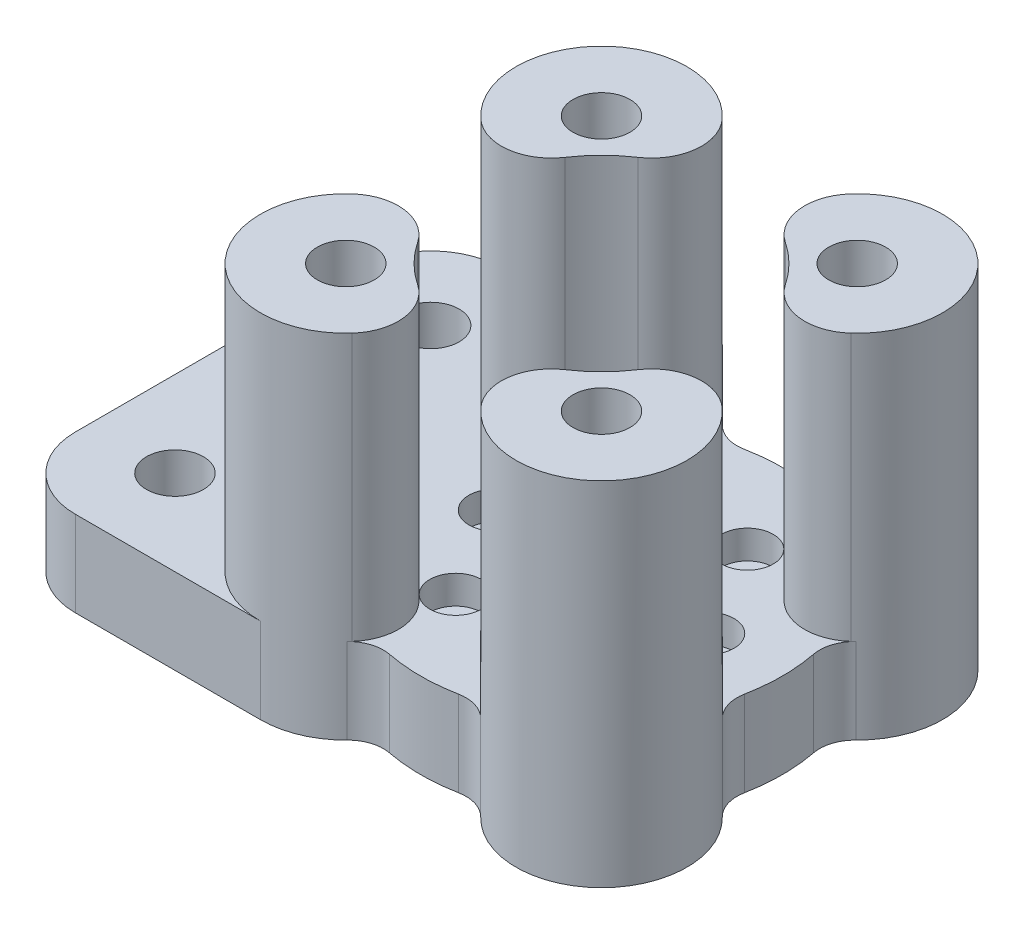
SolidWorks part; units mm, degrees
material "1060 Alloy"
ref_plane "Front" through (0, 0, 0) normal (0, 0, 1) x (1, 0, 0)
ref_plane "Top" through (0, 0, 0) normal (0, 1, 0) x (1, 0, 0)
ref_plane "Right" through (0, 0, 0) normal (1, 0, 0) x (0, 0, -1)
sketch "Sketch1" plane through (0, 0, 0) normal (0, 1, 0) x (1, 0, 0)
  line L0 (0, 0) -> (-17.9605, 17.9605) construction
  line L1 (0, 0) -> (0, 25.4) construction
  line L2 (0, 0) -> (-7.5, 12.9904) construction
  line L3 (-17.9605, 29.9605) -> (-43.9605, 29.9605)
  line L4 (-53.9605, 19.9605) -> (-53.9605, -19.9605)
  line L5 (-43.9605, -29.9605) -> (-17.9605, -29.9605)
  circle A0 centre (-17.9605, 17.9605) radius 4
  circle A1 centre (17.9605, 17.9605) radius 4
  circle A2 centre (17.9605, -17.9605) radius 4
  circle A3 centre (-17.9605, -17.9605) radius 4
  circle A4 centre (0, 0) radius 10.5
  arc A5 (-9.3775, 26.347) -> (-26.347, 9.3775) centre (-17.9605, 17.9605) ccw construction
  arc A6 (26.347, 9.3775) -> (9.3775, 26.347) centre (17.9605, 17.9605) ccw
  arc A7 (9.3775, -26.347) -> (26.347, -9.3775) centre (17.9605, -17.9605) ccw
  arc A8 (-26.347, -9.3775) -> (-9.3775, -26.347) centre (-17.9605, -17.9605) ccw construction
  arc A9 (-24.9332, 4.8471) -> (-24.9332, -4.8471) centre (0, 0) ccw construction
  arc A10 (-4.8471, -24.9332) -> (4.8471, -24.9332) centre (0, 0) ccw
  arc A11 (24.9332, -4.8471) -> (24.9332, 4.8471) centre (0, 0) ccw
  arc A12 (-4.8471, 24.9332) -> (-9.3775, 26.347) centre (-5.8013, 29.8413) cw
  arc A13 (4.8471, 24.9332) -> (-4.8471, 24.9332) centre (0, 0) ccw
  arc A14 (9.3775, 26.347) -> (4.8471, 24.9332) centre (5.8013, 29.8413) cw
  arc A15 (26.347, 9.3775) -> (24.9332, 4.8471) centre (29.8413, 5.8013) ccw
  arc A16 (24.9332, -4.8471) -> (26.347, -9.3775) centre (29.8413, -5.8013) ccw
  arc A17 (9.3775, -26.347) -> (4.8471, -24.9332) centre (5.8013, -29.8413) ccw
  arc A18 (-4.8471, -24.9332) -> (-9.3775, -26.347) centre (-5.8013, -29.8413) ccw
  arc A19 (-24.9332, -4.8471) -> (-26.347, -9.3775) centre (-29.8413, -5.8013) cw construction
  arc A20 (-24.9332, 4.8471) -> (-26.347, 9.3775) centre (-29.8413, 5.8013) ccw construction
  circle A21 centre (0, 0) radius 15 construction
  circle A22 centre (-7.5, 12.9904) radius 2
  circle A23 centre (7.5, 12.9904) radius 2
  circle A24 centre (15, 0) radius 2
  circle A25 centre (7.5, -12.9904) radius 2
  circle A26 centre (-7.5, -12.9904) radius 2
  circle A27 centre (-15, 0) radius 2
  arc A28 (-9.3775, 26.347) -> (-17.9605, 29.9605) centre (-17.9605, 17.9605) ccw
  arc A29 (-9.3775, -26.347) -> (-17.9605, -29.9605) centre (-17.9605, -17.9605) cw
  circle A30 centre (-41.9605, 17.9605) radius 4
  circle A31 centre (-41.9605, -17.9605) radius 4
  arc A32 (-53.9605, -19.9605) -> (-43.9605, -29.9605) centre (-43.9605, -19.9605) ccw
  arc A33 (-43.9605, 29.9605) -> (-53.9605, 19.9605) centre (-43.9605, 19.9605) ccw
  point P0 (0, 0)
  point P17 (0, 0)
  point P27 (0, 0)
  point P56 (0, 0)
  dimension "D5" = 8
  dimension "D6" = 21
  dimension "D1" = 5
  dimension "D7" = 12
  dimension "D9" = 30
  dimension "D11" = 4
  dimension "D14" = 10
  dimension "D3" = 25.4
  dimension "D2" = 12
  dimension "D10" = 12
  dimension "D13" = 24
  dimension "D4" = 4
  dimension "D8" = 4
  dimension "D12" = 6
extrude "base" add sketch "Sketch1" along normal blind 12
sketch "Sketch2" plane through (0, 12, 0) normal (0, 1, 0) x (1, 0, 0)
  circle A0 centre (0, 0) radius 15 construction
  circle A1 centre (-7.5, 12.9904) radius 3.625
  circle A2 centre (7.5, 12.9904) radius 3.625
  circle A3 centre (15, 0) radius 3.625
  circle A4 centre (7.5, -12.9904) radius 3.625
  circle A5 centre (-7.5, -12.9904) radius 3.625
  circle A7 centre (-15, 0) radius 3.625
  point P15 (0, 0)
  point P17 (0, 0)
  dimension "D1" = 7.25
  dimension "D2" = 6
extrude "bolt head recesses" cut sketch "Sketch2" against normal blind 4
sketch "Sketch3" plane through (0, 12, 0) normal (0, 1, 0) x (1, 0, 0)
  circle A0 centre (-17.9605, -17.9605) radius 4
  arc A1 (-17.6441, -5.9647) -> (-5.9647, -17.6441) centre (-17.9605, -17.9605) ccw
  circle A2 centre (-17.9605, -17.9605) radius 4 construction
  arc A4 (-5.9647, 17.6441) -> (-17.6441, 5.9647) centre (-17.9605, 17.9605) ccw
  circle A5 centre (-17.9605, 17.9605) radius 4
  arc A6 (17.6441, 5.9647) -> (5.9647, 17.6441) centre (17.9605, 17.9605) ccw
  circle A7 centre (17.9605, 17.9605) radius 4
  arc A8 (5.9647, -17.6441) -> (17.6441, -5.9647) centre (17.9605, -17.9605) ccw
  circle A9 centre (17.9605, -17.9605) radius 4
  circle A10 centre (0, 0) radius 25.4 construction
  arc A11 (-17.6441, -5.9647) -> (-5.9647, -17.6441) centre (0, 0) ccw
  circle A12 centre (-7.5, 12.9904) radius 3.625 construction
  arc A13 (-5.9647, 17.6441) -> (-17.6441, 5.9647) centre (0, 0) ccw
  arc A14 (17.6441, 5.9647) -> (5.9647, 17.6441) centre (0, 0) ccw
  arc A15 (5.9647, -17.6441) -> (17.6441, -5.9647) centre (0, 0) ccw
  arc A16 (-17.9605, -29.9605) -> (-9.3775, -26.347) centre (-17.9605, -17.9605) ccw construction
  point P21 (0, 0)
  dimension "D1" = 4
extrude "legs" add sketch "Sketch3" along normal blind 37.5
fillet "Fillet2" radius 7 8 edges at (-17.6441, 30.75, 5.9647) (-5.9647, 30.75, 17.6441) (17.6441, 30.75, 5.9647) (5.9647, 30.75, 17.6441) (17.6441, 30.75, -5.9647) (5.9647, 30.75, -17.6441) (-17.6441, 30.75, -5.9647) (-5.9647, 30.75, -17.6441)
sketch "Sketch4" plane through (0, 0, 0) normal (0, -1, 0) x (1, 0, 0)
  circle A0 centre (0, 0) radius 25.4 construction
  circle A1 centre (17.9605, 17.9605) radius 7
  circle A2 centre (17.9605, -17.9605) radius 7
  circle A3 centre (-17.9605, -17.9605) radius 7
  circle A4 centre (-17.9605, 17.9605) radius 7
  point P16 (0, 0)
  dimension "D1" = 14
  dimension "D2" = 4
extrude "m8 counterbore" cut sketch "Sketch4" against normal blind 8
equation "\"D3@Sketch1\"=\"square plate bolt pattern diameter\"/2"
equation "\"D1@base\" = \"motor mount plate thickness\""
equation "\"D5@Sketch1\"=\"square plate bolt hole ID\""
equation "\"D6@Sketch1\"=\"motor mount coupler hole diameter\""
equation "\"bearing OD\" = 30mm"
equation "\"bearing outer race thickness\"= 1mm"
equation "\"bearing ID\"= 10mm"
equation "\"bearing depth\"= 9mm"
equation "\"bearing inner race thickness\"= 1mm"
equation "\"small seal OD\" = 20mm"
equation "\"small seal ID\"= 8mm"
equation "\"small seal depth\" = 8.3mm"
equation "\"big seal OD\" = 27mm"
equation "\"big seal ID\"= 15mm"
equation "\"big seal depth\"= 8.3mm"
equation "\"z\" = 8 \t\t\t\t'number of blades"
equation "\"de\" = 0.426in \t\t\t\t'entrance eye diameter"
equation "\"d2\" = 2.097in \t\t\t\t'outer diameter of the impeller "
equation "\"d_exit\" = 0.18in \t\t\t'volute throat aka D4"
equation "\"theta\" = 15"
equation "\"b2\" = .071in\t\t\t\t\t\t\t\t'tip height from disc surface at d2"
equation "\"b1\" = \"b2\" + (\"d2\"/2 - \"de\"/2)*sin(\"theta\")\t\t\t\t'tip height from disc surface at inlet eye"
equation "\"s\" = ( 1/\"z\")*(3.14*\"de\" - (3.14*(\"de\"^2) / (4*(\"b1\"))))\t\t'thickness of blades, calculated from area"
equation "\"s_opening\" = (3.14*\"de\" - \"z\"*\"s\")/\"z\"\t\t\t\t\t'ideal gap between blades, calculated from area"
equation "\"area_eye\"=3.14*(\"de\"^2)/4\t\t\t\t\t\t'eye area"
equation "\"single_channel_area\"=\"s_opening\"*\"b1\"\t\t\t\t\t'ideal area between two blades"
equation "\"impeller upper clearance\"= .5mm"
equation "\"impeller horizontal clearance\"= (\"d2\"*1.15 - \"d2\")/2 \t\t\t\t\t'clearance based on D2-D3 ratio for circular volute, ranges 1.15 to 1.2"
equation "\"impeller bottom clearance\"= .5mm"
equation "\"impeller base thickness\"= 2mm"
equation "\"impeller boss depth\" = \"shaft impeller section length\" + 3mm + \"impeller bolt head depth\" - \"impeller base thickness\""
equation "\"impeller boss diameter\" = \"big seal ID\""
equation "\"impeller dowel diameter\" = 2mm"
equation "\"impeller bolt head diameter\" = 7.5mm"
equation "\"impeller bolt head depth\" = 4mm"
equation "\"impeller shaft bore\"= 8mm"
equation "\"impeller shaft bore depth\" = \"impeller boss depth\" + \"impeller base thickness\" - \"impeller bolt head depth\" - 3mm"
equation "\"impeller dowel length\" = 2mm*2 + \"impeller shaft bore\""
equation "\"impeller screw hole bore\" = 4mm"
equation "\"shaft impeller screw hole diameter\" = \"impeller screw hole bore\""
equation "\"shaft impeller section length\" = \"big seal plate thickness\"/2 + \"impeller bottom clearance\" + \"impeller base thickness\" - \"impeller bolt head depth\" - 3mm"
equation "\"shaft impeller screw hole depth\" = \"shaft impeller section length\"-\"impeller dowel diameter\"-2mm"
equation "\"shaft impeller section diameter\" = \"impeller shaft bore\""
equation "\"shaft seal section diameter\"=\"small seal ID\""
equation "\"shaft seal section length\"= \"big seal plate thickness\"/2 + \"small seal bore\" + 2mm"
equation "\"shaft bearing section diameter\" = \"bearing ID\""
equation "\"shaft bearing section length\" = \"bearing bore\""
equation "\"shaft bearing stop diameter\" = \"bearing ID\" + 2mm"
equation "\"shaft bearing stop length\" = 2mm"
equation "\"shaft coupler section diameter\" = 8mm"
equation "\"shaft coupler section length\" = \"shaft bearing stop length\" + \"coupler length\"/2 + 4mm"
equation "\"coupler motor shaft hole ID\"= 8mm"
equation "\"coupler OD\"= 17mm"
equation "\"coupler length\"= 25mm"
equation "\"square plate diameter\" = 3in"
equation "\"square plate bolt pattern diameter\"= 2in"
equation "\"square plate bolt hole ID\" = 8mm"
equation "\"bearing plate bearing stop ID\" = \"bearing OD\" - 4mm"
equation "\"bearing plate bearing stop depth\" = 3mm"
equation "\"bearing plate thickness\" = \"bearing bore\" + \"bearing plate bearing stop depth\""
equation "\"small seal plate lip depth\" = \"shaft bearing stop length\" + 1mm"
equation "\"small seal plate lip ID\" = \"small seal OD\" - 3mm"
equation "\"small seal plate thickness\" = \"small seal plate lip depth\" + \"small seal bore\""
equation "\"big seal plate lip depth\" = 8mm"
equation "\"big seal plate thickness\" = \"big seal plate outer thickness\" + \"big seal plate riser height\""
equation "\"impeller cavity center height\"= \"impeller bottom clearance\" + \"impeller upper clearance\" + \"final impeller center height\""
equation "\"impeller cavity diameter\"= 2 * \"impeller horizontal clearance\" + \"d2\" \t\t\t'called D3 analytically"
equation "\"impeller cavity outer height\"= \"impeller bottom clearance\" + \"impeller upper clearance\" + \"impeller base thickness\" + \"b2\" \t\t\t'this is height at impeller diameter d2, not at d3"
equation "\"impeller housing bolt count\" = 8"
equation "\"impeller housing bolt diameter\" = 6mm"
equation "\"impeller housing bolt pattern diameter\" = 3in"
equation "\"impeller housing o-ring channel height\"= 1.5mm"
equation "\"impeller housing o ring channel width\"= 1.5mm"
equation "\"impeller housing o-ring diameter\" = 2in"
equation "\"impeller housing threaded inlet diameter\" = 0.6875in \t\t\t'this is the 11/16 drill size for 1/2 npt fitting"
equation "\"impeller housing threaded inlet depth\"= 20mm"
equation "\"impeller housing thickness\"= \"impeller housing exit threaded diameter\" + 2*\"impeller housing outlet purchase\""
equation "\"impeller housing exit threaded diameter\"= 0.6875in \t\t\t'this is the 11/16 drill size for 1/2 npt fitting"
equation "\"impeller housing exit threaded depth\"= 12mm"
equation "\"impeller housing diameter\" = 4in"
equation "\"impeller housing diffuser conical angle\"=10"
equation "\"impeller housing diffuser tangent angle\"=0"
equation "\"impeller housing outlet purchase\" = 6mm"
equation "\"motor to housing distance\" = \"motor shaft pride\" + \"shaft coupler section length\" - \"bearing plate bearing stop depth\" + 2mm"
equation "\"motor mount coupler hole diameter\"= \"coupler OD\"+ 4mm"
equation "\"motor mount to housing post radius\"= ( 3 * \"square plate bolt hole ID\" ) / 2"
equation "\"motor mount m4 screw hole diameter\"= 4mm"
equation "\"motor mount m4 head diameter\"= 7.25mm"
equation "\"motor mount m4 head depth\"= 4mm"
equation "\"motor mount plate thickness\"= 8mm + \"motor mount m4 head depth\""
equation "\"motor shaft pride\"= 32mm"
equation "\"motor shaft flat section length from tip\"= 25.7mm"
equation "\"motor shaft bore end clearance\"= 2mm"
equation "\"coupler shaft to motor clearance\" = 2mm"
equation "\"motor mount shaft hole depth\"= \"motor shaft pride\""
equation "\"bit size\"= 1mm"
equation "\"inlet area before cut\" = \"minimum channel width\" * (\"z\") * \"b1\"\t\t\t\t'if minimum channel width>s_opening, this is larger than area_eye"
equation "\"area to cut\" = \"inlet area before cut\" - \"area_eye\"\t\t\t\t\t\t'amount of extra area\t\t\t\t\t"
equation "\"height to cut\" = \"area to cut\" / ((\"z\")* \"minimum channel width\")+ .0001in\t\t\t'the 0.0001 in cut is to avoid errors in model"
equation "\"final impeller center height\" = \"impeller base thickness\" + \"b1\" - \"height to cut\"\t\t'corrected height so that sum of channel areas equals eye area"
equation "\"D7@Sketch1\"=\"square plate bolt hole ID\"*3/2"
equation "\"motor mount m4 pattern diamater\" = 30mm"
equation "\"D9@Sketch1\"=\"motor mount m4 pattern diamater\""
equation "\"D11@Sketch1\"=\"motor mount m4 screw hole diameter\""
equation "\"D1@Sketch2\"=\"motor mount m4 head diameter\""
equation "\"D1@bolt head recesses\" = \"motor mount m4 head depth\""
equation "\"D1@legs\" = \"motor to housing distance\" - \"motor mount plate thickness\""
